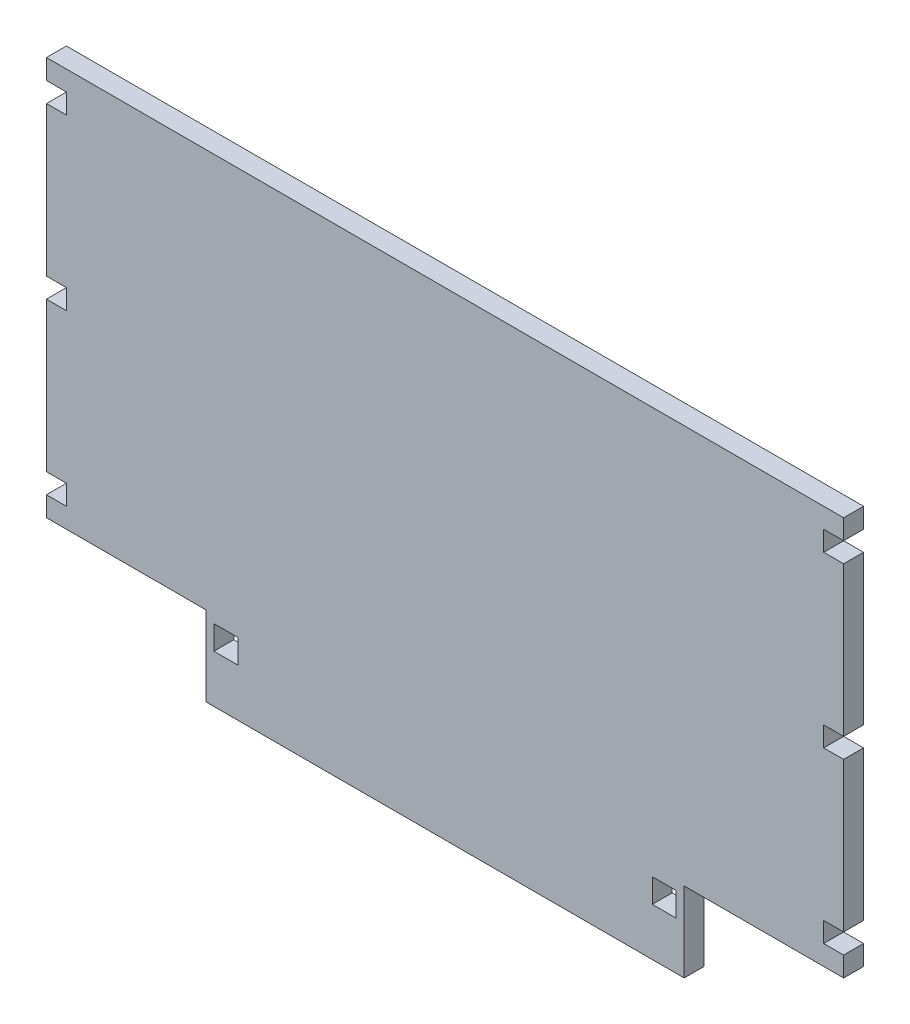
SolidWorks part; units mm, degrees
ref_plane "Front Plane" through (0, 0, 0) normal (0, 0, 1) x (1, 0, 0)
ref_plane "Top Plane" through (0, 0, 0) normal (0, 1, 0) x (1, 0, 0)
ref_plane "Right Plane" through (0, 0, 0) normal (1, 0, 0) x (0, 0, -1)
sketch "Sketch2" plane through (0, 0, 0) normal (0, 0, 1) x (1, 0, 0)
  line L0 (-100, -75) -> (-100, -45)
  line L1 (-100, 75) -> (100, 75)
  line L2 (-100, 75) -> (-100, -75)
  line L3 (-100, -75) -> (100, -75)
  line L4 (100, 75) -> (100, -75)
  line L5 (-100, 75) -> (100, -75) construction
  line L6 (-100, -75) -> (100, 75) construction
  line L7 (-100, -45) -> (-60, -45)
  line L8 (-60, -45) -> (-60, -75)
  line L9 (100, -75) -> (100, -45)
  line L10 (100, -45) -> (60, -45)
  line L11 (60, -45) -> (60, -75)
  line L12 (-60, -75) -> (-60, -65)
  line L13 (-60, -65) -> (60, -65)
  line L14 (-60, -45) -> (-50, -45)
  line L15 (-50, -45) -> (-50, -55)
  line L16 (-50, -55) -> (-60, -55)
  line L17 (60, -45) -> (50, -45)
  line L18 (50, -45) -> (50, -55)
  line L19 (50, -55) -> (60, -55)
  line L20 (-55, -55) -> (-55, -50)
  line L21 (-55, -50) -> (-50, -50)
  line L22 (-50, -45) -> (-52, -45)
  line L23 (-50, -45) -> (-50, -47)
  line L24 (0, -65) -> (0, -61.3332)
  line L25 (-58, -53) -> (-52, -53)
  line L26 (-58, -53) -> (-58, -47)
  line L27 (-58, -47) -> (-52, -47)
  line L28 (-52, -53) -> (-52, -47)
  line L29 (-58, -53) -> (-52, -47) construction
  line L30 (-58, -47) -> (-52, -53) construction
  line L31 (58, -47) -> (52, -47)
  line L32 (52, -53) -> (52, -47)
  line L33 (58, -53) -> (52, -53)
  line L34 (58, -53) -> (58, -47)
  point P0 (0, 0)
  dimension "D1" = 200
  dimension "D2" = 150
  dimension "D3" = 40
extrude "Boss-Extrude1" add sketch "Sketch2" along normal blind 5
sketch "Sketch3" plane through (0, 0, 5) normal (0, 0, 1) x (1, 0, 0)
  line L0 (-100, 75) -> (-100, -45) construction
  line L1 (-100, 75) -> (-100, 55)
  line L2 (-100, 55) -> (100, 55)
  line L3 (100, 75) -> (100, -45) construction
  line L4 (100, 55) -> (100, 75)
  line L5 (100, 75) -> (-100, 75)
extrude "Cut-Extrude1" cut sketch "Sketch3" against normal blind 5
sketch "Sketch4" plane through (0, 0, 0) normal (0, 0, -1) x (-1, 0, 0)
  line L0 (-100, 55) -> (100, 55)
  line L1 (100, 55) -> (100, -45)
  line L2 (100, -45) -> (-100, -45)
  line L3 (-100, -45) -> (-100, 55)
  line L4 (100, 55) -> (95, 55)
  line L5 (95, 55) -> (95, -45)
  line L6 (95, -45) -> (100, -45)
  line L7 (100, 55) -> (100, 45)
  line L8 (100, 45) -> (95, 45)
  line L9 (95, 45) -> (95, 50)
  line L10 (95, 50) -> (100, 50)
  line L11 (100, 50) -> (99, 50)
  line L12 (100, 50) -> (100, 49)
  line L13 (97.5, 45) -> (97.5, 47.5)
  line L14 (100, 5) -> (95, 5)
  line L15 (96, 46) -> (99, 46)
  line L16 (96, 46) -> (96, 49)
  line L17 (96, 49) -> (99, 49)
  line L18 (99, 46) -> (99, 49)
  line L19 (96, 46) -> (99, 49) construction
  line L20 (96, 49) -> (99, 46) construction
  line L21 (96, -39) -> (99, -39)
  line L22 (99, -36) -> (99, -39)
  line L23 (96, -36) -> (99, -36)
  line L24 (96, -36) -> (96, -39)
  line L25 (100, 5) -> (100, 7.5)
  line L26 (100, 5) -> (100, 2.5)
  line L27 (100, 2.5) -> (95, 2.5)
  line L28 (95, 2.5) -> (95, 7.5)
  line L29 (95, 7.5) -> (100, 7.5)
  line L30 (100, 2.5) -> (99, 2.5)
  line L31 (100, 2.5) -> (100, 3.5)
  line L32 (0, -45) -> (0, -36)
  line L33 (96, 6.5) -> (99, 6.5)
  line L34 (96, 6.5) -> (96, 3.5)
  line L35 (96, 3.5) -> (99, 3.5)
  line L36 (99, 6.5) -> (99, 3.5)
  line L37 (96, 6.5) -> (99, 3.5) construction
  line L38 (96, 3.5) -> (99, 6.5) construction
  line L39 (97.5, -36) -> (97.5, -39)
  line L40 (100, 50) -> (95, 50)
  line L41 (100, 50) -> (100, 45)
  line L42 (100, 45) -> (95, 45)
  line L43 (95, 50) -> (95, 45)
  line L44 (100, 50) -> (95, 45) construction
  line L45 (100, 45) -> (95, 50) construction
  line L46 (97.5, -39) -> (97.5, -40)
  line L47 (-100, 45) -> (-95, 45)
  line L48 (100, -35) -> (95, -35)
  line L49 (100, -35) -> (100, -40)
  line L50 (100, -40) -> (95, -40)
  line L51 (95, -35) -> (95, -40)
  line L52 (100, -35) -> (95, -40) construction
  line L53 (100, -40) -> (95, -35) construction
  line L54 (-95, 50) -> (-95, 45)
  line L55 (-100, 50) -> (-95, 50)
  line L56 (-100, 50) -> (-100, 45)
  line L57 (-100, 5) -> (-100, 7.5)
  line L58 (-95, 7.5) -> (-100, 7.5)
  line L59 (-95, 2.5) -> (-95, 7.5)
  line L60 (-100, 2.5) -> (-95, 2.5)
  line L61 (-100, 5) -> (-100, 2.5)
  line L62 (-100, -40) -> (-95, -40)
  line L63 (-95, -35) -> (-95, -40)
  line L64 (-100, -35) -> (-95, -35)
  line L65 (-100, -35) -> (-100, -40)
  point P31 (97.5, 5)
  point P44 (97.5, -37.5)
extrude "Cut-Extrude2" cut sketch "Sketch4" against normal blind 5
